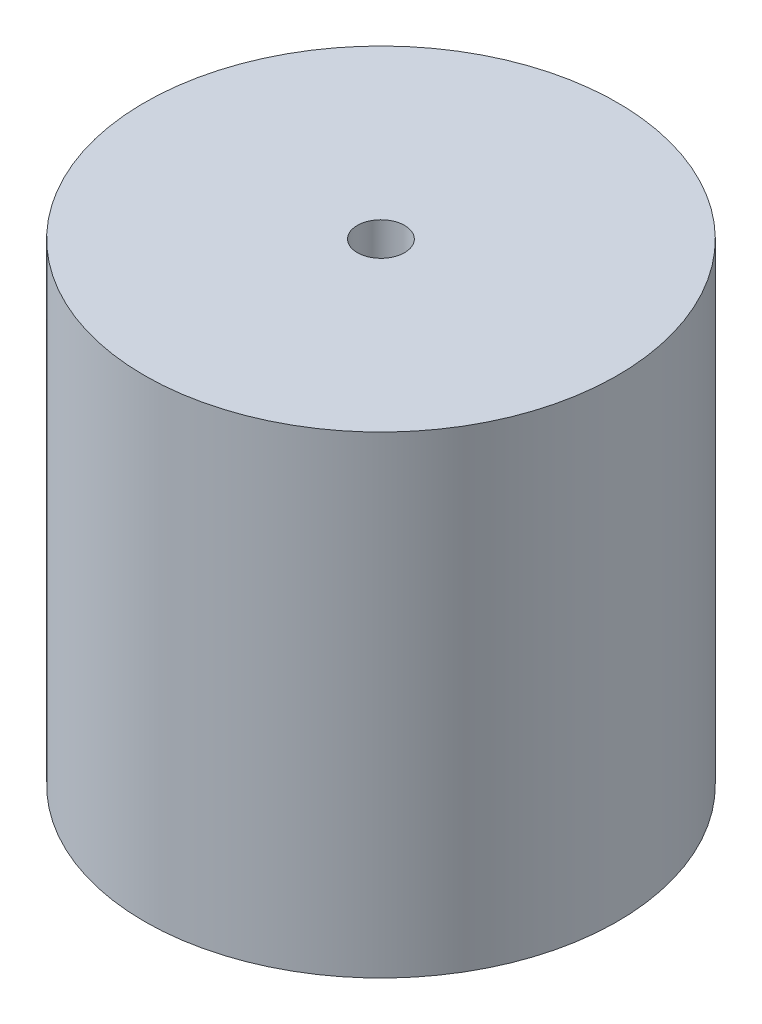
SolidWorks part; units mm, degrees
ref_plane "Front Plane" through (0, 0, 0) normal (0, 0, 1) x (1, 0, 0)
ref_plane "Top Plane" through (0, 0, 0) normal (0, 1, 0) x (1, 0, 0)
ref_plane "Right Plane" through (0, 0, 0) normal (1, 0, 0) x (0, 0, -1)
sketch "Sketch2" plane through (0, 0, 0) normal (0, 1, 0) x (1, 0, 0)
  circle A0 centre (0, 0) radius 15.875
  dimension "D1" = 31.75
extrude "Boss-Extrude1" add sketch "Sketch2" along normal blind 31.75
sketch "Sketch3" plane through (0, 0, 0) normal (0, -1, 0) x (1, 0, 0)
  circle A0 centre (0, 0) radius 12.065
  dimension "D1" = 24.13
extrude "Cut-Extrude1" cut sketch "Sketch3" against normal blind 24.13
sketch "Sketch4" plane through (0, 31.75, 0) normal (0, 1, 0) x (1, 0, 0)
  circle A0 centre (0, 0) radius 1.5875
  dimension "D1" = 3.175
extrude "Cut-Extrude2" cut sketch "Sketch4" against normal up to next
